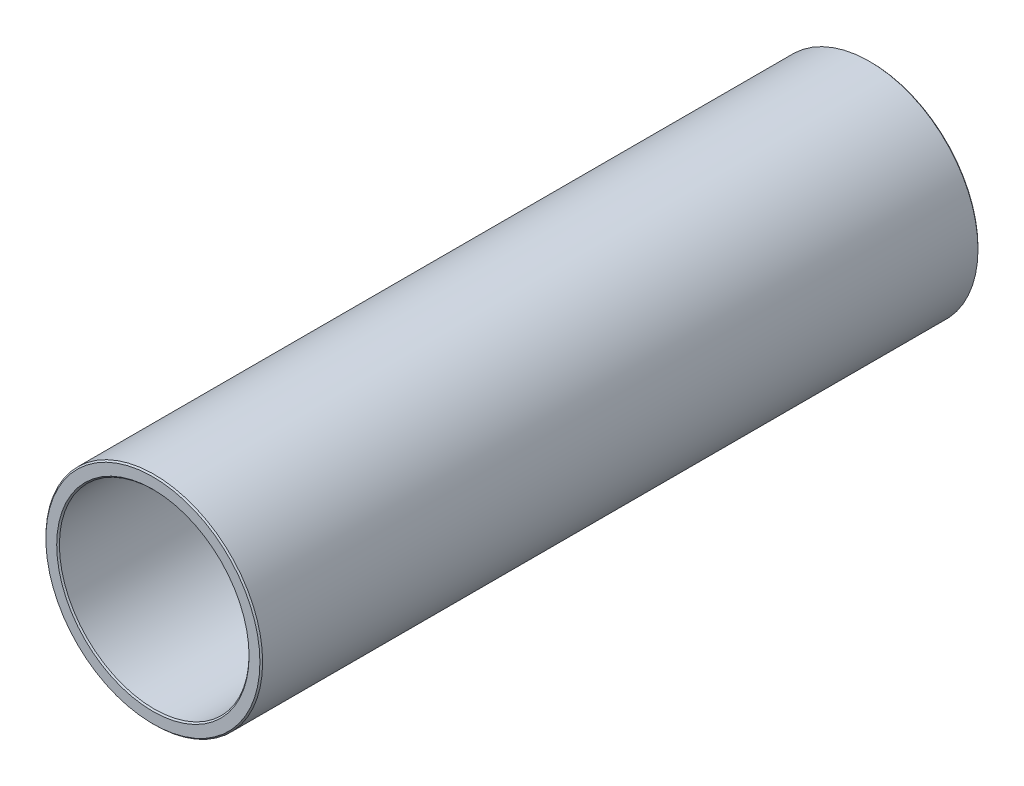
SolidWorks part; units mm, degrees
material "镀铬不锈钢"
ref_plane "前视基准面" through (0, 0, 0) normal (0, 0, 1) x (1, 0, 0)
ref_plane "上视基准面" through (0, 0, 0) normal (0, 1, 0) x (1, 0, 0)
ref_plane "右视基准面" through (0, 0, 0) normal (1, 0, 0) x (0, 0, -1)
sketch "Sketch1" plane through (0, 0, 0) normal (0, 0, 1) x (1, 0, 0)
  circle A0 centre (0, 0) radius 7
  circle A1 centre (0, 0) radius 8
  dimension "D1" = 14
  dimension "D2" = 16
extrude "Extrude1" add sketch "Sketch1" along normal blind 53
chamfer "Chamfer1" distance 0.1 angle 45 4 edges at (7, 0, 0) (8, 0, 0) (7, 0, 53) (8, 0, 53)
